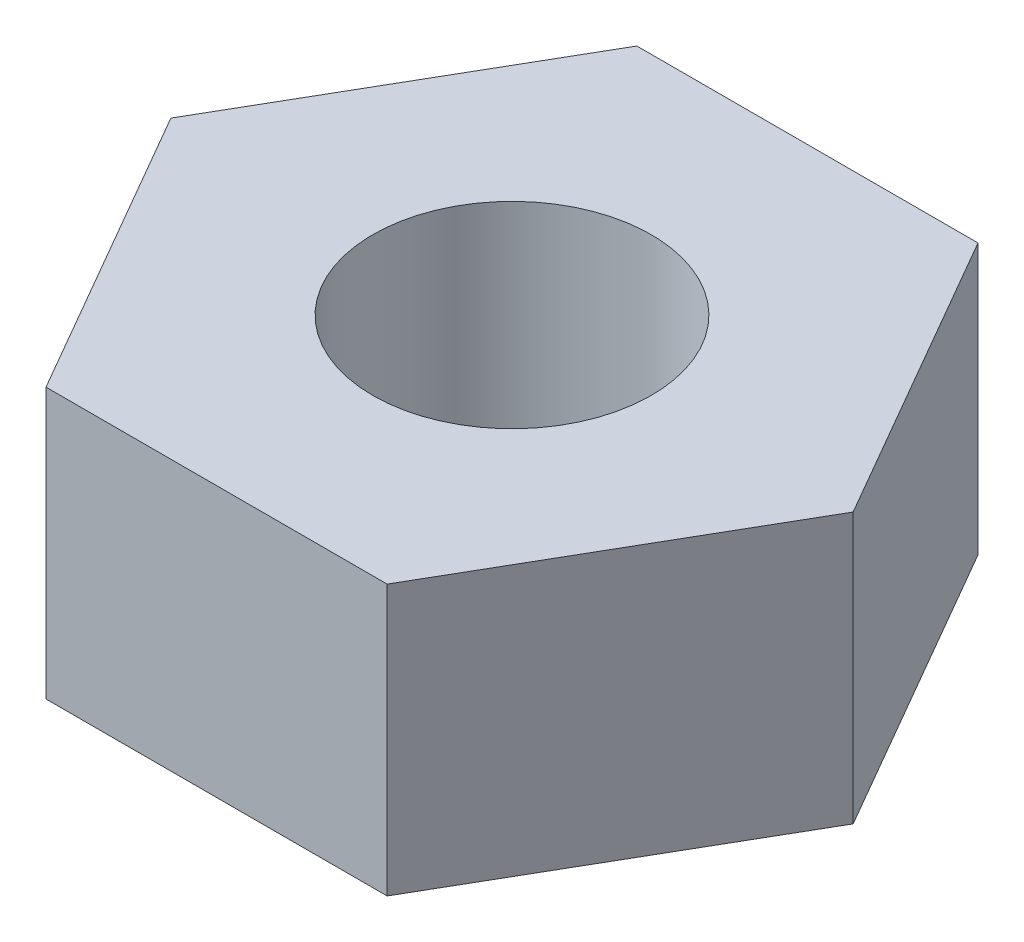
SolidWorks part; units mm, degrees
ref_plane "Front Plane" through (0, 0, 0) normal (0, 0, 1) x (1, 0, 0)
ref_plane "Top Plane" through (0, 0, 0) normal (0, 1, 0) x (1, 0, 0)
ref_plane "Right Plane" through (0, 0, 0) normal (1, 0, 0) x (0, 0, -1)
sketch "Sketch1" plane through (0, 0, 0) normal (0, 1, 0) x (1, 0, 0)
  line L1 (-4.0415, 0) -> (-2.0207, -3.5)
  line L2 (-2.0207, -3.5) -> (2.0207, -3.5)
  line L3 (2.0207, -3.5) -> (4.0415, 0)
  line L4 (4.0415, 0) -> (2.0207, 3.5)
  line L5 (2.0207, 3.5) -> (-2.0207, 3.5)
  line L6 (-2.0207, 3.5) -> (-4.0415, 0)
  circle A0 centre (0, 0) radius 2
  circle A2 centre (0, 0) radius 3.5 construction
  point P3 (0, 0)
  dimension "D1" = 4
  dimension "D2" = 7
extrude "Boss-Extrude1" add sketch "Sketch1" along normal blind 3.2 contours A0 | L5 L6 L1 L2 L3 L4 A0
sketch "Sketch3" plane through (0, 3.2, 0) normal (0, 1, 0) x (1, 0, 0)
  point P0 (0, 0)
hole_wizard "Tap Drill for M4x0.7 Tap1" positions "Sketch3" profile "Sketch4" hole size "M4x0.7" standard "ANSI Metric" end condition through all
sketch "Sketch4" plane through (0, 3.2, 0) normal (1, 0, 0) x (0, 0, 1)
  line L0 (0, 0) -> (0, 3.2)
  line L1 (0, 3.2) -> (1.65, 3.2)
  line L2 (1.65, 3.2) -> (1.65, 0)
  line L5 (1.65, 0) -> (0, 0)
  line L11 (0, -6.35) -> (0, 107.95) construction
  dimension "Thru Hole Dia." = 3.3
  dimension "Thru Hole Depth" = 3.2
